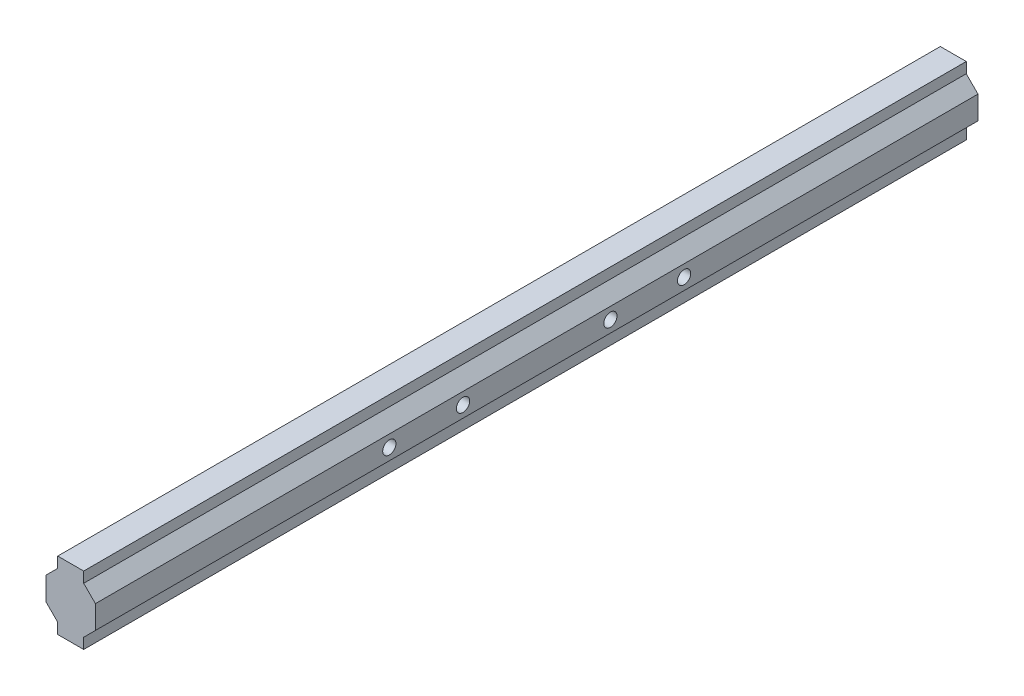
SolidWorks part; units mm, degrees
ref_plane "Front Plane" through (0, 0, 0) normal (0, 0, 1) x (1, 0, 0)
ref_plane "Top Plane" through (0, 0, 0) normal (0, 1, 0) x (1, 0, 0)
ref_plane "Right Plane" through (0, 0, 0) normal (1, 0, 0) x (0, 0, -1)
sketch "Sketch1" plane through (0, 0, 116.1066) normal (0, 0, 1) x (1, 0, 0)
  line L0 (-39.5503, 5.2942) -> (-36.8896, 7.9549)
  line L1 (-36.8896, 7.9549) -> (-36.8896, 10.362)
  line L2 (-36.8896, 10.362) -> (-31.011, 10.362)
  line L3 (-31.011, 7.9549) -> (-28.3503, 5.2942)
  line L4 (-28.3503, 5.2942) -> (-28.3503, 0.0298)
  line L5 (-28.3503, 0.0298) -> (-31.011, -2.6309)
  line L6 (-31.011, -2.6309) -> (-31.011, -5.038)
  line L7 (-31.011, -5.038) -> (-36.8896, -5.038)
  line L8 (-36.8896, -5.038) -> (-36.8896, -2.6309)
  line L9 (-36.8896, -2.6309) -> (-39.5503, 0.0298)
  line L10 (-39.5503, 0.0298) -> (-39.5503, 5.2942)
  line L11 (-31.011, 10.362) -> (-31.011, 7.9549)
  line L12 (-37.3896, 10.862) -> (-30.511, 10.862) construction
  line L13 (-37.3896, -5.538) -> (-30.511, -5.538) construction
  line L14 (-27.8503, 5.4185) -> (-27.8503, -0.0945) construction
  line L15 (-40.0503, 5.4185) -> (-40.0503, -0.0945) construction
  line L16 (-39.9917, 5.5599) -> (-37.3896, 8.162) construction
  line L17 (-37.3896, 8.162) -> (-37.3896, 10.862) construction
  line L18 (-30.511, 8.162) -> (-30.511, 10.862) construction
  line L19 (-27.9089, 5.5599) -> (-30.511, 8.162) construction
  line L20 (-27.9089, -0.2359) -> (-30.511, -2.838) construction
  line L21 (-30.511, -2.838) -> (-30.511, -5.538) construction
  line L22 (-37.3896, -2.838) -> (-37.3896, -5.538) construction
  line L23 (-39.9917, -0.2359) -> (-37.3896, -2.838) construction
  point P24 (-37.3896, 9.512)
  dimension "D1" = 0.5
  dimension "D2" = 0.5
  dimension "D3" = 0.5
  dimension "D4" = 0.5
  dimension "D5" = 0.5
  dimension "D6" = 0.5
  dimension "D7" = 0.5
  dimension "D8" = 0.5
  dimension "D9" = 0.5
  dimension "D10" = 0.5
  dimension "D11" = 0.5
  dimension "D12" = 0.5
extrude "Boss-Extrude1" add sketch "Sketch1" along normal blind 200
sketch "Sketch2" plane through (-28.3503, 0, 0) normal (1, 0, 0) x (0, 0, -1)
  line L0 (-316.1066, 5.2942) -> (-116.1066, 5.2942) construction
  line L1 (-316.1066, 0.0298) -> (-316.1066, 5.2942) construction
  line L3 (-216.1066, 5.2942) -> (-216.1066, -8.2415) construction
  circle A0 centre (-232.8066, 2.662) radius 1.5
  circle A1 centre (-249.5066, 2.662) radius 1.5
  circle A2 centre (-199.4066, 2.662) radius 1.5
  circle A3 centre (-182.7066, 2.662) radius 1.5
  point P6 (-216.1066, 5.2942)
  point P9 (-316.1066, 2.662)
  point P14 (-256.5263, 47.4715)
  dimension "D1" = 16.7
  dimension "D2" = 3
  dimension "D3" = 3
  dimension "D4" = 16.7
  dimension "D5" = 0
  dimension "D6" = 0
extrude "Cut-Extrude1" cut sketch "Sketch2" against normal blind 20
